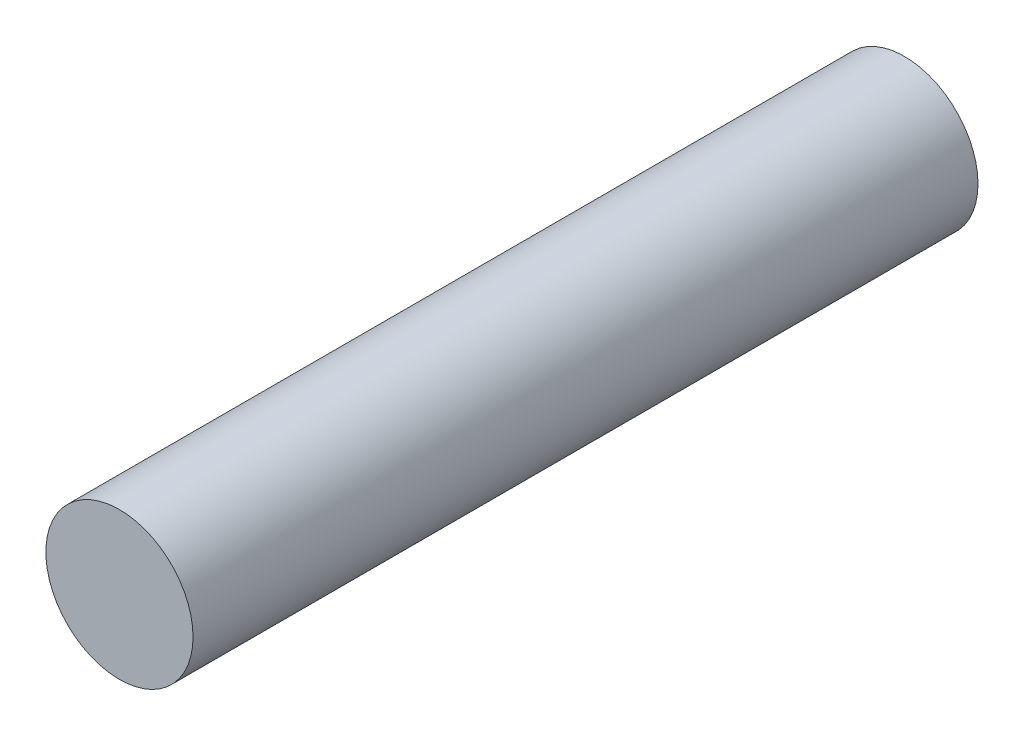
SolidWorks part; units mm, degrees
material "ASTM A36 Steel"
ref_plane "Front Plane" through (0, 0, 0) normal (0, 0, 1) x (1, 0, 0)
ref_plane "Top Plane" through (0, 0, 0) normal (0, 1, 0) x (1, 0, 0)
ref_plane "Right Plane" through (0, 0, 0) normal (1, 0, 0) x (0, 0, -1)
sketch "Sketch2" plane through (0, 0, 0) normal (0, 0, 1) x (1, 0, 0)
  circle A0 centre (0, 0) radius 2.25
  dimension "D1" = 4.5
extrude "Boss-Extrude1" add sketch "Sketch2" along normal blind 24
